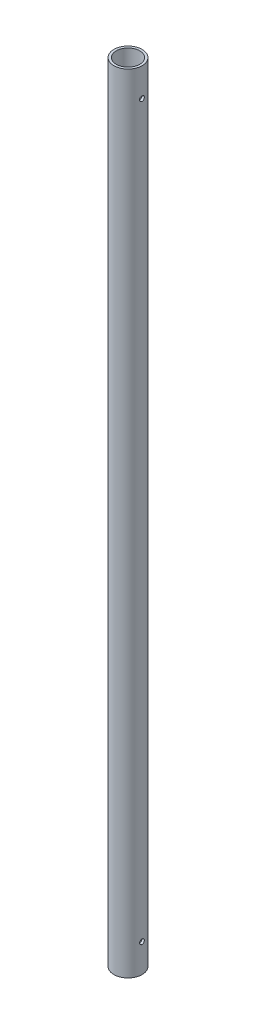
SolidWorks part; units mm, degrees
ref_plane "Front Plane" through (0, 0, 0) normal (0, 0, 1) x (1, 0, 0)
ref_plane "Top Plane" through (0, 0, 0) normal (0, 1, 0) x (1, 0, 0)
ref_plane "Right Plane" through (0, 0, 0) normal (1, 0, 0) x (0, 0, -1)
sketch "Sketch2" plane through (0, 0, 0) normal (0, 1, 0) x (1, 0, 0)
  circle A0 centre (0, 0) radius 21.082
  circle A1 centre (0, 0) radius 17.526
  dimension "D1" = 42.164
  dimension "D2" = 35.052
extrude "Boss-Extrude1" add sketch "Sketch2" along normal mid plane 1174.75
hole_wizard "1/4 Clearance Hole1" positions "3DSketch1" profile "Sketch3" hole size "1/4" standard "ANSI Inch" end condition through all
sketch3d "3DSketch1"
  line L2 (0, 0, 0) -> (21.082, 0, 0) construction
  point P23 (21.082, -544.83, 0)
  point P25 (21.082, 544.83, 0)
  dimension "D1" = 42.545
  dimension "D2" = 42.545
sketch "Sketch3" plane through (21.082, 544.83, 0) normal (0, 1, 0) x (0, 0, -1)
  line L0 (0, 0) -> (0, 42.164)
  line L1 (0, 42.164) -> (3.5712, 42.164)
  line L2 (3.5712, 42.164) -> (3.5712, 0)
  line L5 (3.5712, 0) -> (0, 0)
  line L11 (0, -6.35) -> (0, 107.95) construction
  dimension "Thru Hole Dia." = 7.1425
  dimension "Thru Hole Depth" = 42.164
